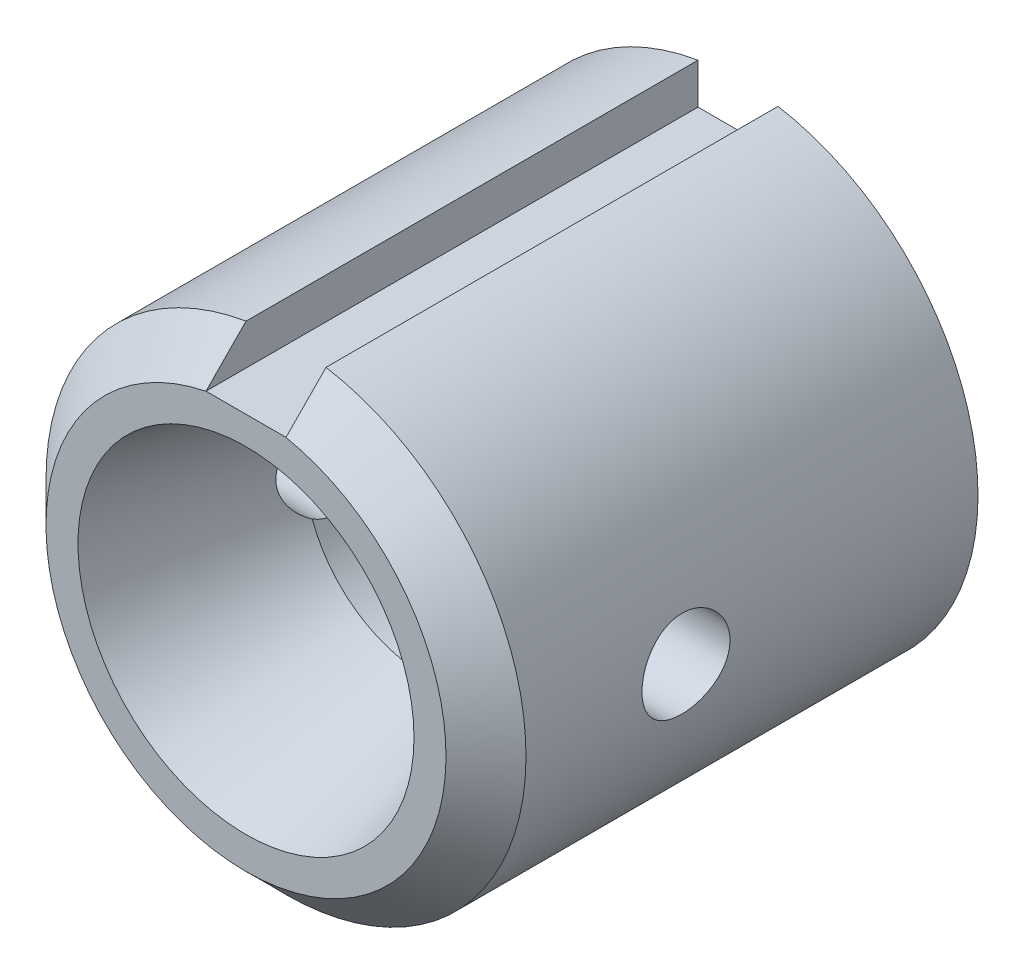
SolidWorks part; units mm, degrees
material "Plain Carbon Steel"
ref_plane "Front Plane" through (0, 0, 0) normal (0, 0, 1) x (1, 0, 0)
ref_plane "Top Plane" through (0, 0, 0) normal (0, 1, 0) x (1, 0, 0)
ref_plane "Right Plane" through (0, 0, 0) normal (1, 0, 0) x (0, 0, -1)
ref_plane "Plane1" through (0, 295, 0) normal (0, 1, 0) x (-1, 0, 0)
sketch "Sketch1" plane through (0, 295, 0) normal (0, 1, 0) x (-1, 0, 0)
  line L0 (-66, 6.7) -> (-60, 6.7)
  line L1 (-60, 6.7) -> (-60, 19)
  line L2 (-60, 19) -> (-66, 19)
  line L3 (-66, 19) -> (-66, 6.7)
  line L4 (-60, 6.7) -> (-60, 19) construction
revolve "Revolve1" add sketch "Sketch1" angle 360 about L4
sketch "Sketch2" plane through (0, 0, 6.7) normal (0, 0, -1) x (-1, 0, 0)
  line L0 (-61, 300.9161) -> (-61, 299.9)
  line L1 (-61, 299.9) -> (-59, 299.9)
  line L2 (-59, 299.9) -> (-59, 300.9161)
  arc A0 (-59, 300.9161) -> (-61, 300.9161) centre (-60, 295) ccw
  dimension "D1" = 2
extrude "Extrude1" cut sketch "Sketch2" against normal through all
hole_wizard "Hole1" positions "Sketch4" profile "Sketch3" legacy
sketch "Sketch4" plane through (0, 0, 6.7) normal (0, 0, -1) x (-1, 0, 0)
  point P0 (-60, 295)
sketch "Sketch3" plane through (60, 295, 6.7) normal (1, 0, 0) x (0, 1, 0)
  line L0 (0, 0) -> (0, 12.3)
  line L1 (0, 12.3) -> (3, 12.3)
  line L2 (3, 12.3) -> (3, 0)
  line L3 (3, 0) -> (0, 0)
  line L4 (0, 110) -> (0, -10) construction
  dimension "Diameter" = 6
  dimension "Depth" = 12.3
chamfer "Chamfer1" distance 1 angle 45 1 edges at (60, 289, 19)
sketch "Sketch5" plane through (0, 0, 0) normal (1, 0, 0) x (0, 0, -1)
  line L0 (-19, 294.95) -> (-14, 294.95) construction
  line L1 (-19, 299.9) -> (-19, 290) construction
  circle A0 centre (-14, 294.95) radius 1.1
  dimension "D2" = 2.2
  dimension "D1" = 5
extrude "Extrude3" cut sketch "Sketch5" along normal blind 80
sketch "Sketch6" plane through (0, 0, 19) normal (0, 0, 1) x (1, 0, 0)
  circle A0 centre (60, 295) radius 4.2
  circle A1 centre (60, 295) radius 3 construction
  dimension "D1" = 8.4
extrude "Extrude4" cut sketch "Sketch6" against normal blind 10 draft 15
